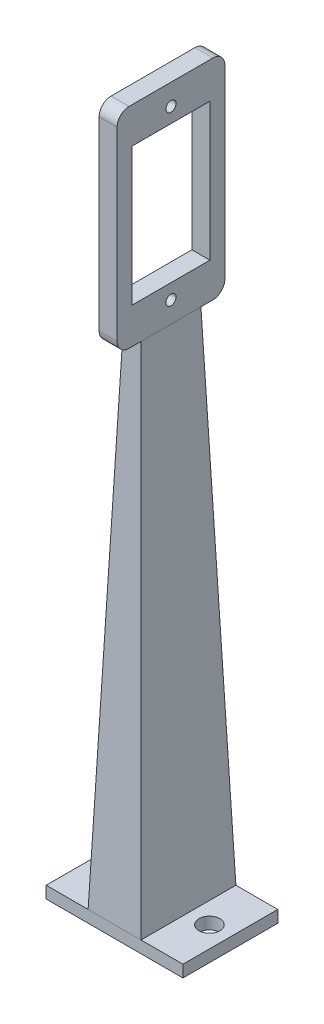
SolidWorks part; units mm, degrees
ref_plane "Plano frontal" through (0, 0, 0) normal (0, 0, 1) x (1, 0, 0)
ref_plane "Plano superior" through (0, 0, 0) normal (0, 1, 0) x (1, 0, 0)
ref_plane "Plano direito" through (0, 0, 0) normal (1, 0, 0) x (0, 0, -1)
sketch "Esboço1" plane through (0, 0, 0) normal (1, 0, 0) x (0, 0, -1)
  line L1 (-9, -17.5) -> (9, -17.5)
  line L2 (-9, -17.5) -> (-9, 17.5)
  line L3 (-9, 17.5) -> (9, 17.5)
  line L4 (9, -17.5) -> (9, 17.5)
  line L5 (-9, -17.5) -> (9, 17.5) construction
  line L6 (-9, 17.5) -> (9, -17.5) construction
  point P0 (0, 0)
  dimension "D1" = 35
  dimension "D2" = 18
extrude "Ressalto-extrusão1" add sketch "Esboço1" along normal mid plane 3
sketch "Esboço2" plane through (1.5, 0, 0) normal (1, 0, 0) x (0, 0, -1)
  line L1 (6.5, -11.5) -> (-6.5, -11.5)
  line L2 (6.5, -11.5) -> (6.5, 11.5)
  line L3 (6.5, 11.5) -> (-6.5, 11.5)
  line L4 (-6.5, -11.5) -> (-6.5, 11.5)
  line L5 (6.5, -11.5) -> (-6.5, 11.5) construction
  line L6 (6.5, 11.5) -> (-6.5, -11.5) construction
  point P0 (0, 0)
  dimension "D1" = 13
  dimension "D2" = 23
extrude "Corte-extrusão1" cut sketch "Esboço2" against normal up to next
sketch "Esboço3" plane through (-1.5, 0, 0) normal (-1, 0, 0) x (0, 0, 1)
  line L0 (-12.3301, 0) -> (12.3301, 0) construction
  circle A0 centre (0, 14) radius 0.85
  circle A1 centre (0, -14) radius 0.85
  dimension "D1" = 1.7
  dimension "D2" = 14
extrude "Corte-extrusão2" cut sketch "Esboço3" against normal up to next
fillet "Filete1" radius 2 4 edges at (0, -17.5, 9) (0, -17.5, -9) (0, 17.5, 9) (0, 17.5, -9)
sketch "Esboço4" plane through (0, -17.5, 0) normal (0, -1, 0) x (1, 0, 0)
  line L1 (-1.5, 5) -> (1.5, 5)
  line L2 (-1.5, 5) -> (-1.5, -5)
  line L3 (-1.5, -5) -> (1.5, -5)
  line L4 (1.5, 5) -> (1.5, -5)
  line L5 (1.5, 7) -> (1.5, -7) construction
  line L6 (-1.5, 7) -> (-1.5, -7) construction
  point P9 (1.5, 0)
  dimension "D1" = 10
extrude "Ressalto-extrusão2" add sketch "Esboço4" along normal blind 83.68 draft 2
sketch "Esboço5" plane through (0, -101.18, 0) normal (0, -1, 0) x (1, 0, 0)
  line L0 (-4.4222, -7.9222) -> (4.4222, -7.9222) construction
  line L1 (-11.4222, 7.9222) -> (11.4222, 7.9222)
  line L2 (-11.4222, 7.9222) -> (-11.4222, -7.9222)
  line L3 (-11.4222, -7.9222) -> (11.4222, -7.9222)
  line L4 (11.4222, 7.9222) -> (11.4222, -7.9222)
  line L6 (4.4222, 7.9222) -> (-4.4222, 7.9222) construction
  line L7 (4.4222, -7.9222) -> (4.4222, 7.9222) construction
  point P13 (0, 7.9222)
  dimension "D1" = 7
extrude "Ressalto-extrusão3" add sketch "Esboço5" along normal blind 2
sketch "Esboço6" plane through (0, -101.18, 0) normal (0, 1, 0) x (1, 0, 0)
  line L0 (0, 5.4735) -> (0, -5.791) construction
  line L1 (-11.4222, -7.9222) -> (-11.4222, 7.9222) construction
  circle A0 centre (7.9222, 0) radius 1.75
  circle A1 centre (-7.9222, 0) radius 1.75
  dimension "D1" = 3.5
  dimension "D2" = 3.5
extrude "Corte-extrusão3" cut sketch "Esboço6" against normal up to next
